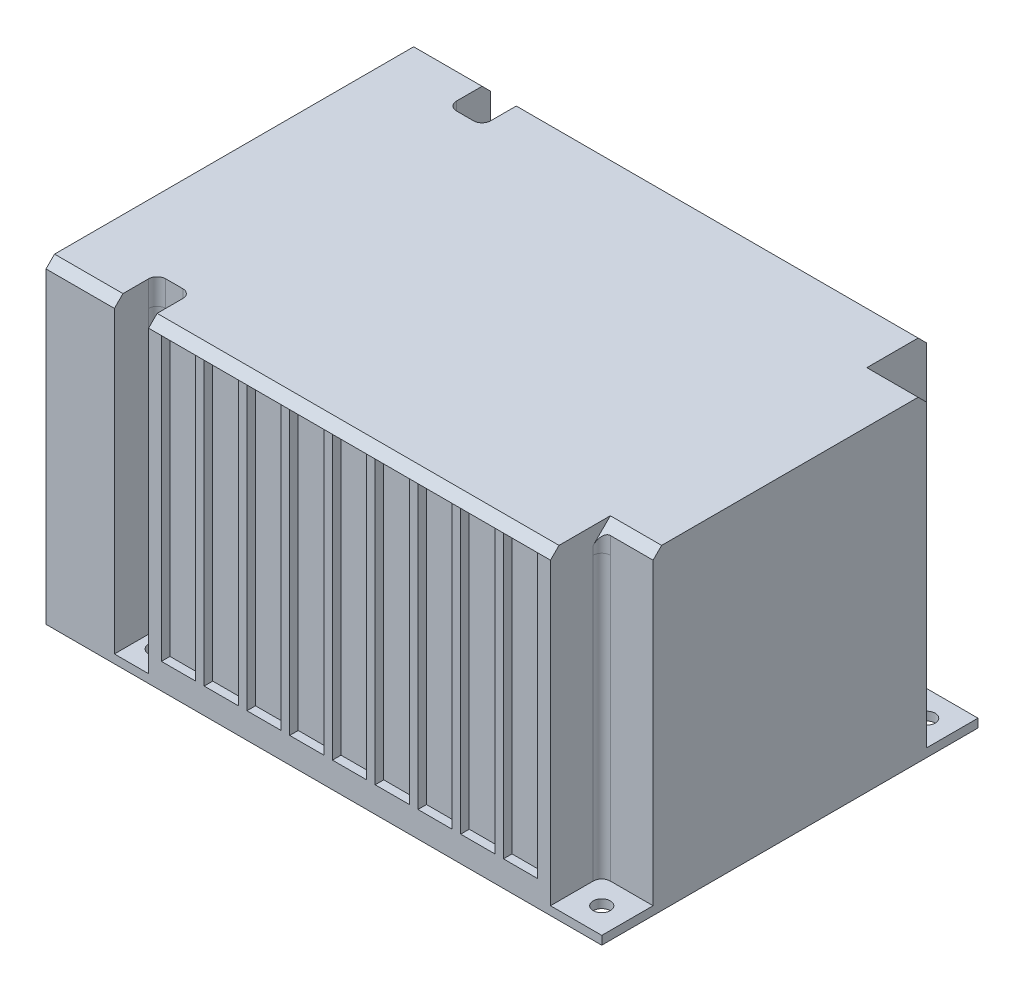
SolidWorks part; units mm, degrees
ref_plane "Спереди" through (0, 0, 0) normal (0, 0, 1) x (1, 0, 0)
ref_plane "Сверху" through (0, 0, 0) normal (0, 1, 0) x (1, 0, 0)
ref_plane "Справа" through (0, 0, 0) normal (1, 0, 0) x (0, 0, -1)
sketch "Sketch1" plane through (0, 0, 0) normal (0, 1, 0) x (1, 0, 0)
  line L2 (-43.2119, -60) -> (-63.2119, -60)
  line L3 (106.7881, 0) -> (106.7881, 60)
  line L4 (106.7881, 60) -> (-43.2119, 60)
  line L5 (-43.2119, -60) -> (106.7881, -60)
  line L6 (106.7881, -60) -> (106.7881, 0)
  line L7 (-63.2119, -60) -> (-63.2119, 60)
  line L8 (-63.2119, 60) -> (-43.2119, 60)
  line L9 (-63.2119, -60) -> (-63.2119, -52.5)
  line L10 (-63.2119, -52.5) -> (-55.7119, -52.5)
  line L12 (162.5, 80) -> (162.5, -80)
  line L14 (-122.5, 100) -> (-122.5, 110)
  line L15 (-162.5, 110) -> (-162.5, 100)
  line L16 (-112.5, 85) -> (-102.5, 85)
  line L17 (-112.5, 85) -> (-122.5, 85)
  line L18 (-122.5, 85) -> (-122.5, 100)
  line L20 (-102.5, 85) -> (-102.5, 100)
  line L21 (156.131, 0) -> (-49843.869, 0)
  line L22 (-132.5, 85) -> (-132.5, 95)
  line L23 (-132.5, 85) -> (-132.5, 75)
  line L24 (-132.5, 75) -> (-93.0036, 75)
  line L25 (-93.0036, 75) -> (-93.0036, 100)
  line L26 (-93.0036, 100) -> (122.5, 100)
  line L27 (152.5, 70) -> (122.5, 70)
  line L28 (132.5, 95) -> (132.5, 100)
  line L29 (147.5, 80) -> (152.5, 80)
  line L30 (132.5, 95) -> (132.5, 80)
  line L31 (132.5, 80) -> (147.5, 80)
  line L32 (-162.5, 110) -> (-122.5, 110)
  line L33 (-102.5, 100) -> (-102.5, 110)
  line L34 (-102.5, 110) -> (132.5, 110)
  line L35 (152.5, 80) -> (162.5, 80)
  line L36 (122.5, 70) -> (122.5, 100)
  line L37 (132.5, 100) -> (132.5, 110)
  line L38 (152.5, 70) -> (152.5, -70)
  line L39 (132.5, -100) -> (132.5, -110)
  line L40 (122.5, -70) -> (122.5, -100)
  line L41 (152.5, -80) -> (162.5, -80)
  line L42 (-102.5, -110) -> (132.5, -110)
  line L43 (-102.5, -100) -> (-102.5, -110)
  line L44 (-162.5, -110) -> (-122.5, -110)
  line L45 (132.5, -80) -> (147.5, -80)
  line L46 (132.5, -95) -> (132.5, -80)
  line L47 (147.5, -80) -> (152.5, -80)
  line L48 (132.5, -95) -> (132.5, -100)
  line L49 (152.5, -70) -> (122.5, -70)
  line L50 (-93.0036, -100) -> (122.5, -100)
  line L51 (-93.0036, -75) -> (-93.0036, -100)
  line L52 (-132.5, -75) -> (-93.0036, -75)
  line L53 (-132.5, -85) -> (-132.5, -75)
  line L54 (-132.5, -85) -> (-132.5, -95)
  line L55 (-102.5, -85) -> (-102.5, -100)
  line L57 (-122.5, -85) -> (-122.5, -100)
  line L58 (-112.5, -85) -> (-122.5, -85)
  line L59 (-112.5, -85) -> (-102.5, -85)
  line L60 (-162.5, -110) -> (-162.5, -100)
  line L61 (-122.5, -100) -> (-122.5, -110)
  line L62 (-162.5, 100) -> (-162.5, 95)
  line L63 (-162.5, 95) -> (-132.5, 95)
  line L64 (-162.5, -95) -> (-132.5, -95)
  line L65 (-162.5, -100) -> (-162.5, -95)
  circle A0 centre (147.5, -95) radius 5
  circle A2 centre (-112.5, -95) radius 5
  circle A6 centre (67.5, -105) radius 3
  circle A7 centre (-32.5, -105) radius 3
  circle A9 centre (157.5, -35) radius 3
  circle A10 centre (-55.7119, -52.5) radius 5
  circle A11 centre (99.2881, -52.5) radius 5
  circle A12 centre (99.2881, 52.5) radius 5
  circle A13 centre (-55.7119, 52.5) radius 5
  circle A14 centre (-112.5, 95) radius 5
  point P18 (162.5, 0)
  point P20 (152.5, 0)
extrude "Boss-Extrude1" add sketch "Sketch1" along normal blind 170 contours L51 L50 L40 L49 L38 L27 L36 L26 L25 L24 L23 L22 L63 L62 L15 L32 L14 L18 L17 L16 L20 L33 L34 L37 L28 L30 L31 L29 L35 L12 L41 L47 L45 L46 L48 L39 L42 L43 L55 L59 L58 L57 L61 L44 L60 L65 L64 L54 L53 L52
sketch "Sketch3" plane through (0, 0, 0) normal (0, 1, 0) x (1, 0, 0)
  line L0 (-122.5, -110) -> (-102.5, -110)
  line L1 (132.5, -110) -> (162.5, -110)
  line L2 (162.5, -110) -> (162.5, -80)
  line L3 (162.5, -80) -> (132.5, -80)
  line L4 (132.5, -80) -> (132.5, -110)
  line L5 (-122.5, -110) -> (-122.5, -85)
  line L6 (-122.5, -85) -> (-102.5, -85)
  line L7 (-102.5, -85) -> (-102.5, -110)
  line L8 (0, 0) -> (-187.8265, 0)
  line L9 (-102.5, 85) -> (-102.5, 110)
  line L10 (-122.5, 85) -> (-102.5, 85)
  line L11 (-122.5, 110) -> (-122.5, 85)
  line L12 (132.5, 80) -> (132.5, 110)
  line L13 (162.5, 80) -> (132.5, 80)
  line L14 (162.5, 110) -> (162.5, 80)
  line L15 (132.5, 110) -> (162.5, 110)
  line L16 (-122.5, 110) -> (-102.5, 110)
  line L17 (147.5, -80) -> (147.5, -95)
  circle A0 centre (-112.5, -95) radius 5
  circle A1 centre (147.5, -95) radius 5
  circle A2 centre (147.5, 95) radius 5
  circle A3 centre (-112.5, 95) radius 5
  point P35 (0, 0)
extrude "Boss-Extrude2" add sketch "Sketch3" along normal blind 5
fillet "Fillet1" radius 5 6 edges at (-122.5, 87.5, -85) (-102.5, 87.5, -85) (132.5, 87.5, -80) (132.5, 87.5, 80) (-102.5, 87.5, 85) (-122.5, 87.5, 85)
sketch "Sketch5" plane through (-132.5, 0, 0) normal (-1, 0, 0) x (0, 0, 1)
  line L0 (0, 75) -> (0, 111.3496)
  circle A1 centre (-85, 5) radius 3
  circle A2 centre (85, 5) radius 3
  circle A4 centre (-85, 165) radius 3
  circle A5 centre (85, 165) radius 3
  point P1 (0, 0)
  point P2 (0, 0)
  point P3 (0, 0)
  point P9 (0, 75)
extrude "Cut-Extrude1" cut sketch "Sketch5" against normal blind 3
sketch "Sketch10" plane through (0, 170, 0) normal (0, 1, 0) x (1, 0, 0)
  line L7 (-162.5, 95) -> (-162.5, -95)
  line L9 (162.5, 80) -> (162.5, -80)
  line L10 (-122.5, 100) -> (-122.5, 110)
  line L11 (-162.5, 110) -> (-162.5, 100)
  line L12 (-112.5, 85) -> (-102.5, 85)
  line L13 (-112.5, 85) -> (-122.5, 85)
  line L14 (-122.5, 85) -> (-122.5, 100)
  line L15 (-102.5, 85) -> (-102.5, 100)
  line L16 (43.9708, 0) -> (-49956.0292, 0)
  line L23 (132.5, 95) -> (132.5, 100)
  line L24 (147.5, 80) -> (152.5, 80)
  line L25 (132.5, 95) -> (132.5, 80)
  line L26 (132.5, 80) -> (147.5, 80)
  line L27 (-162.5, 110) -> (-122.5, 110)
  line L28 (-102.5, 100) -> (-102.5, 110)
  line L29 (-102.5, 110) -> (132.5, 110)
  line L30 (152.5, 80) -> (162.5, 80)
  line L32 (132.5, 100) -> (132.5, 110)
  line L34 (132.5, -100) -> (132.5, -110)
  line L36 (152.5, -80) -> (162.5, -80)
  line L37 (-102.5, -110) -> (132.5, -110)
  line L38 (-102.5, -100) -> (-102.5, -110)
  line L39 (-162.5, -110) -> (-122.5, -110)
  line L40 (132.5, -80) -> (147.5, -80)
  line L41 (132.5, -95) -> (132.5, -80)
  line L42 (147.5, -80) -> (152.5, -80)
  line L43 (132.5, -95) -> (132.5, -100)
  line L50 (-102.5, -85) -> (-102.5, -100)
  line L51 (-122.5, -85) -> (-122.5, -100)
  line L52 (-112.5, -85) -> (-122.5, -85)
  line L53 (-112.5, -85) -> (-102.5, -85)
  line L54 (-162.5, -110) -> (-162.5, -100)
  line L55 (-122.5, -100) -> (-122.5, -110)
  line L56 (-162.5, 100) -> (-162.5, 95)
  line L59 (-162.5, -100) -> (-162.5, -95)
  circle A0 centre (147.5, -95) radius 5
  circle A1 centre (-112.5, -95) radius 5
  circle A2 centre (67.5, -105) radius 3
  circle A3 centre (-32.5, -105) radius 3
  circle A4 centre (157.5, -35) radius 3
  circle A9 centre (-112.5, 95) radius 5
  point P18 (162.5, 0)
  point P20 (152.5, 0)
extrude "Boss-Extrude5" add sketch "Sketch10" along normal blind 15 contours L7 L59 L54 L39 L55 L51 L52 L53 L50 L38 L37 L34 L43 L41 L40 L42 L36 L9 L30 L24 L26 L25 L23 L32 L29 L28 L15 L12 L13 L14 L10 L27 L11 L56
chamfer "Chamfer1" distance 5 angle 45 6 edges at (-142.5, 185, -110) (15, 185, -110) (147.5, 185, -80) (147.5, 185, 80) (15, 185, 110) (-142.5, 185, 110)
fillet "Fillet2" radius 5 6 edges at (-122.5, 177.5, -85) (-102.5, 177.5, -85) (132.5, 175, -80) (132.5, 175, 80) (-102.5, 177.5, 85) (-122.5, 177.5, 85)
sketch "Sketch15" plane through (0, 0, 0) normal (0, -1, 0) x (1, 0, 0)
  line L16 (156.131, 0) -> (-49843.869, 0)
  circle A2 centre (67.5, -105) radius 3
  circle A3 centre (-32.5, -105) radius 3
  circle A4 centre (157.5, -35) radius 3
  circle A10 centre (157.5, 35) radius 3
  circle A11 centre (67.5, 105) radius 3
  circle A12 centre (-32.5, 105) radius 3
extrude "Cut-Extrude2" cut sketch "Sketch15" against normal blind 5
sketch "Sketch16" plane through (-162.5, 0, 0) normal (-1, 0, 0) x (0, 0, 1)
  line L5 (-102.5, 177.5) -> (-102.3249, 177.2134)
  circle A0 centre (-102.5, 177.5) radius 3
  circle A1 centre (-102.5, 115.83) radius 3
  circle A2 centre (-102.5, 54.16) radius 3
  circle A3 centre (-34.17, 177.5) radius 3
  circle A4 centre (34.16, 177.5) radius 3
  circle A5 centre (102.49, 177.5) radius 3
  circle A6 centre (102.5, 54.16) radius 3
  circle A7 centre (102.5, 115.83) radius 3
  dimension "D1" = 3
  dimension "D2" = 4
extrude "Cut-Extrude3" cut sketch "Sketch16" against normal blind 5 contours A3 | A4 | A5 | A7 | A6 | A2 | A1 | A0
sketch "Sketch18" plane through (0, 0, 110) normal (0, 0, 1) x (1, 0, 0)
  line L2 (-162.5, 0) -> (162.5, 0) construction
  line L3 (-100, 0) -> (-95, 0)
  line L5 (132.5, 180) -> (-102.5, 180) construction
  line L7 (-75, 0) -> (-70, 0)
  line L11 (-50, 0) -> (-45, 0)
  line L12 (-45, 15) -> (-45, 180)
  line L15 (-25, 0) -> (-20, 0)
  line L16 (-20, 15) -> (-20, 180)
  line L19 (0, 0) -> (5, 0)
  line L20 (5, 15) -> (5, 180)
  line L23 (25, 0) -> (30, 0)
  line L24 (30, 15) -> (30, 180)
  line L25 (30, 180) -> (25, 180)
  line L27 (50, 0) -> (55, 0)
  line L28 (55, 15) -> (55, 180)
  line L31 (75, 0) -> (80, 0)
  line L32 (80, 15) -> (80, 180)
  line L35 (100, 0) -> (105, 0)
  line L38 (125, 180) -> (125, 15)
  line L39 (125, 0) -> (130, 0)
  line L42 (-70, 180) -> (-70, 15)
  line L44 (-95, 180) -> (-95, 15)
  line L45 (-95, 0) -> (-75, 0)
  line L46 (-75, 180) -> (-75, 15)
  line L48 (-50, 180) -> (-50, 15)
  line L49 (-70, 0) -> (-50, 0)
  line L50 (-45, 180) -> (-45, 15)
  line L51 (-45, 180) -> (-25, 180)
  line L52 (-25, 180) -> (-25, 15)
  line L53 (-45, 0) -> (-25, 0)
  line L54 (-20, 180) -> (-20, 15)
  line L55 (-20, 180) -> (0, 180)
  line L56 (0, 180) -> (0, 15)
  line L57 (-20, 0) -> (0, 0)
  line L58 (5, 180) -> (5, 15)
  line L59 (5, 180) -> (25, 180)
  line L60 (25, 180) -> (25, 15)
  line L61 (5, 0) -> (25, 0)
  line L62 (30, 180) -> (30, 15)
  line L63 (30, 180) -> (50, 180)
  line L64 (50, 180) -> (50, 15)
  line L65 (30, 0) -> (50, 0)
  line L66 (55, 180) -> (55, 15)
  line L67 (55, 180) -> (75, 180)
  line L68 (75, 180) -> (75, 15)
  line L69 (55, 0) -> (75, 0)
  line L70 (80, 180) -> (80, 15)
  line L71 (80, 180) -> (100, 180)
  line L72 (100, 180) -> (100, 15)
  line L73 (80, 0) -> (100, 0)
  line L74 (105, 180) -> (105, 15)
  line L75 (105, 180) -> (125, 180)
  line L76 (125, 180) -> (125, 15)
  line L77 (105, 0) -> (125, 0)
  line L78 (-95, 15) -> (-75, 15)
  line L79 (-20, 15) -> (0, 15)
  line L80 (-70, 15) -> (-50, 15)
  line L81 (-45, 15) -> (-25, 15)
  line L82 (5, 15) -> (25, 15)
  line L83 (30, 15) -> (50, 15)
  line L84 (55, 15) -> (75, 15)
  line L85 (80, 15) -> (100, 15)
  line L86 (105, 15) -> (125, 15)
  line L87 (-70, 180) -> (-50, 180)
  line L90 (-95, 180) -> (-75, 180)
  line M6 (132.5, 180) -> (-102.5, 180)
  dimension "D1" = 10
  dimension "D2" = 9
extrude "Cut-Extrude9" cut sketch "Sketch18" against normal blind 5 contours L12 L81 L52 M6 | L16 L79 L56 M6 | L20 L82 L60 M6 | L24 L83 L64 M6 | L28 L84 L68 M6 | L32 L85 L72 M6 | L74 L86 L38 M6 | L46 L78 L44 L90 | L42 L80 L48 L87
sketch "Sketch21" plane through (0, 0, -110) normal (0, 0, -1) x (-1, 0, 0)
  line L0 (-125, 15) -> (-105, 15)
  line L5 (-75, 15) -> (-75, 180)
  line L7 (-50, 15) -> (-50, 180)
  line L9 (-25, 15) -> (-25, 180)
  line L11 (0, 15) -> (0, 180)
  line L12 (0, 180) -> (-5, 180)
  line L14 (25, 15) -> (25, 180)
  line L16 (50, 15) -> (50, 180)
  line L18 (95, 180) -> (95, 15)
  line L20 (-100, 180) -> (-100, 15)
  line L21 (-125, 180) -> (-125, 15)
  line L23 (-105, 180) -> (-105, 15)
  line L24 (-80, 180) -> (-80, 15)
  line L26 (-75, 180) -> (-75, 15)
  line L27 (-75, 180) -> (-55, 180)
  line L28 (-55, 180) -> (-55, 15)
  line L30 (-50, 180) -> (-50, 15)
  line L31 (-50, 180) -> (-30, 180)
  line L32 (-30, 180) -> (-30, 15)
  line L34 (-25, 180) -> (-25, 15)
  line L35 (-25, 180) -> (-5, 180)
  line L36 (-5, 180) -> (-5, 15)
  line L38 (0, 180) -> (0, 15)
  line L39 (0, 180) -> (20, 180)
  line L40 (20, 180) -> (20, 15)
  line L42 (25, 180) -> (25, 15)
  line L43 (25, 180) -> (45, 180)
  line L44 (45, 180) -> (45, 15)
  line L46 (50, 180) -> (50, 15)
  line L47 (50, 180) -> (70, 180)
  line L48 (70, 180) -> (70, 15)
  line L50 (75, 180) -> (75, 15)
  line L51 (75, 180) -> (95, 180)
  line L52 (95, 180) -> (95, 15)
  line L55 (-50, 15) -> (-30, 15)
  line L56 (-100, 15) -> (-80, 15)
  line L57 (-75, 15) -> (-55, 15)
  line L58 (-25, 15) -> (-5, 15)
  line L59 (0, 15) -> (20, 15)
  line L60 (25, 15) -> (45, 15)
  line L61 (50, 15) -> (70, 15)
  line L62 (75, 15) -> (95, 15)
  line L63 (-100, 180) -> (-80, 180)
  line L64 (-125, 180) -> (-105, 180)
  line M30 (102.5, 180) -> (-132.5, 180)
extrude "Cut-Extrude10" cut sketch "Sketch21" against normal blind 5 contours L20 L56 L24 M30 | L5 L57 L28 M30 | L7 L55 L32 M30 | L9 L58 L36 M30 | L11 L59 L40 M30 | L14 L60 L44 M30 | L16 L61 L48 M30 | L50 L62 L18 M30 | L23 L0 L21 L64
